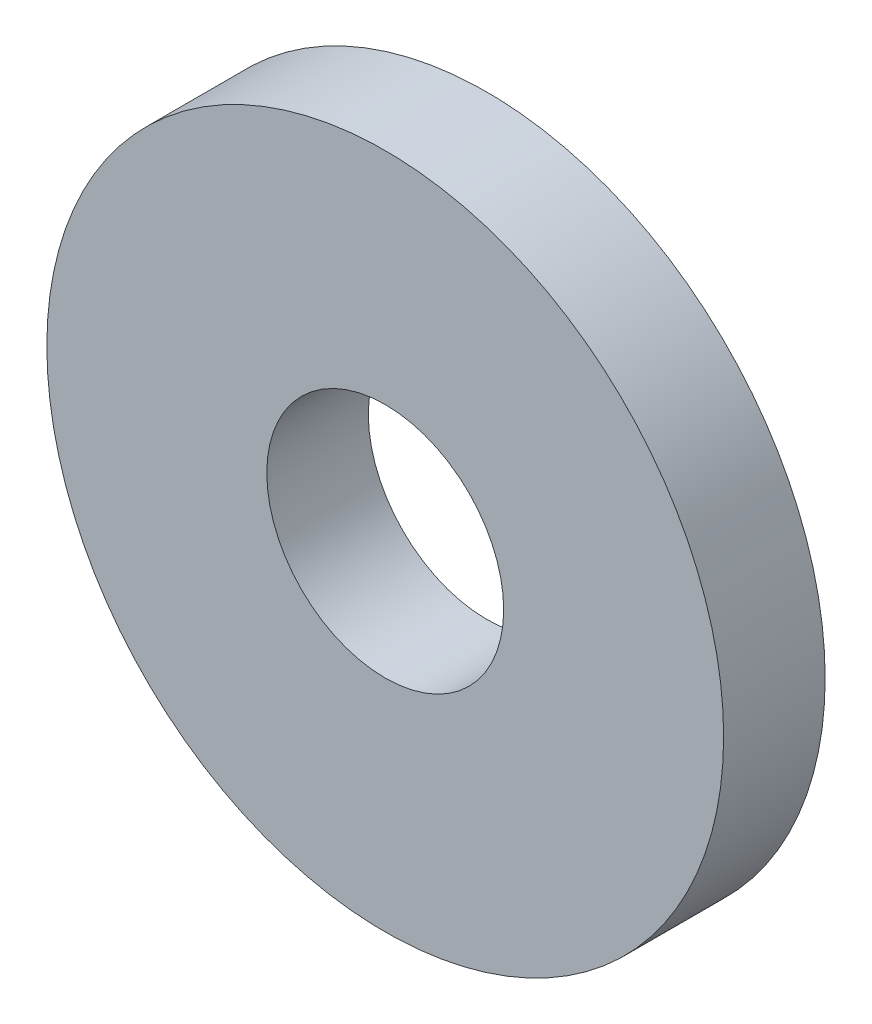
SolidWorks part; units mm, degrees
ref_plane "Front Plane" through (0, 0, 0) normal (0, 0, 1) x (1, 0, 0)
ref_plane "Top Plane" through (0, 0, 0) normal (0, 1, 0) x (1, 0, 0)
ref_plane "Right Plane" through (0, 0, 0) normal (1, 0, 0) x (0, 0, -1)
sketch "Sketch1" plane through (0, 0, 0) normal (0, 0, 1) x (1, 0, 0)
  circle A0 centre (0, 0) radius 10
  circle A1 centre (0, 0) radius 3.5
  dimension "D1" = 7
  dimension "D2" = 20
extrude "Boss-Extrude1" add sketch "Sketch1" along normal blind 3
